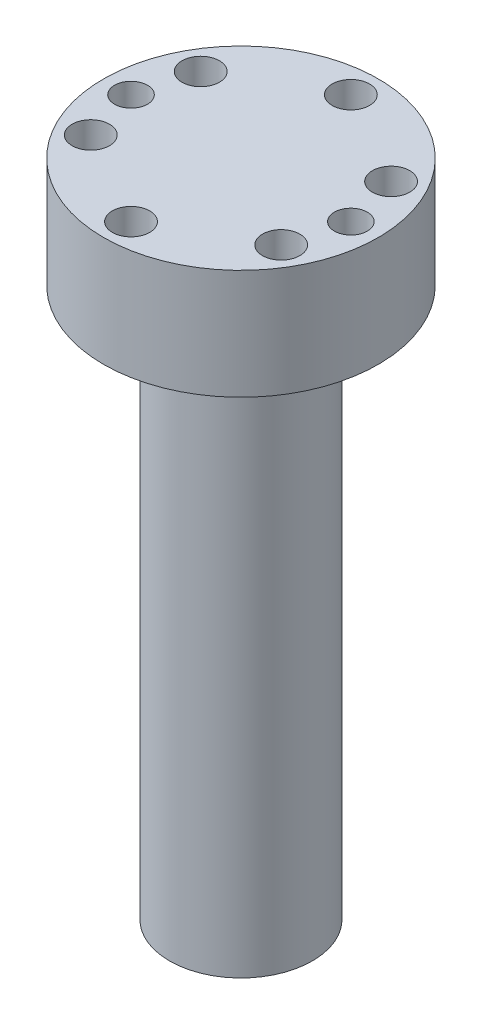
SolidWorks part; units mm, degrees
material "6061-T6 (SS)"
ref_plane "Front Plane" through (0, 0, 0) normal (0, 0, 1) x (1, 0, 0)
ref_plane "Top Plane" through (0, 0, 0) normal (0, 1, 0) x (1, 0, 0)
ref_plane "Right Plane" through (0, 0, 0) normal (1, 0, 0) x (0, 0, -1)
sketch "Sketch1" plane through (0, 0, 0) normal (0, 1, 0) x (1, 0, 0)
  circle A0 centre (0, 0) radius 12.5
  dimension "D1" = 25
extrude "Boss-Extrude1" add sketch "Sketch1" along normal blind 10
sketch "Sketch2" plane through (0, 10, 0) normal (0, 1, 0) x (1, 0, 0)
  circle A0 centre (0, 0) radius 10
  point P4 (0, 10)
  point P10 (8.6603, 5)
  point P11 (8.6603, -5)
  point P12 (0, -10)
  point P13 (-8.6603, -5)
  point P14 (-8.6603, 5)
  dimension "D1" = 20
  dimension "D2" = 6
hole_wizard "M3 Clearance Hole1" positions "Sketch2" profile "Sketch3" hole size "M3" standard "DIN" end condition through all
sketch "Sketch3" plane through (-8.6603, 10, -5) normal (1, 0, 0) x (0, 0, 1)
  line L0 (0, 0) -> (0, 10)
  line L1 (0, 10) -> (1.7, 10)
  line L2 (1.7, 10) -> (1.7, 0)
  line L5 (1.7, 0) -> (0, 0)
  line L11 (0, -6.35) -> (0, 107.95) construction
  dimension "Thru Hole Dia." = 3.4
  dimension "Thru Hole Depth" = 10
sketch "Sketch4" plane through (0, 10, 0) normal (0, 1, 0) x (1, 0, 0)
  circle A0 centre (0, 0) radius 10
  point P6 (10, 0)
  point P8 (-10, 0)
hole_wizard "Ø3.0mm Dowel Hole1" positions "Sketch4" profile "Sketch6" hole size "Ø3.0" standard "DIN" end condition through all
sketch "Sketch6" plane through (-10, 10, 0) normal (1, 0, 0) x (0, 0, 1)
  line L0 (0, 0) -> (0, 10)
  line L1 (0, 10) -> (1.5, 10)
  line L2 (1.5, 10) -> (1.5, 0)
  line L5 (1.5, 0) -> (0, 0)
  line L11 (0, -6.35) -> (0, 107.95) construction
  dimension "Thru Hole Dia." = 3
  dimension "Thru Hole Depth" = 10
sketch "Sketch7" plane through (0, 0, 0) normal (0, 1, 0) x (1, 0, 0)
  circle A0 centre (0, 0) radius 6.5
  circle A1 centre (0, 10) radius 3.5 construction
  dimension "D1" = 7
  dimension "D2" = 13
extrude "Boss-Extrude2" add sketch "Sketch7" against normal blind 50
